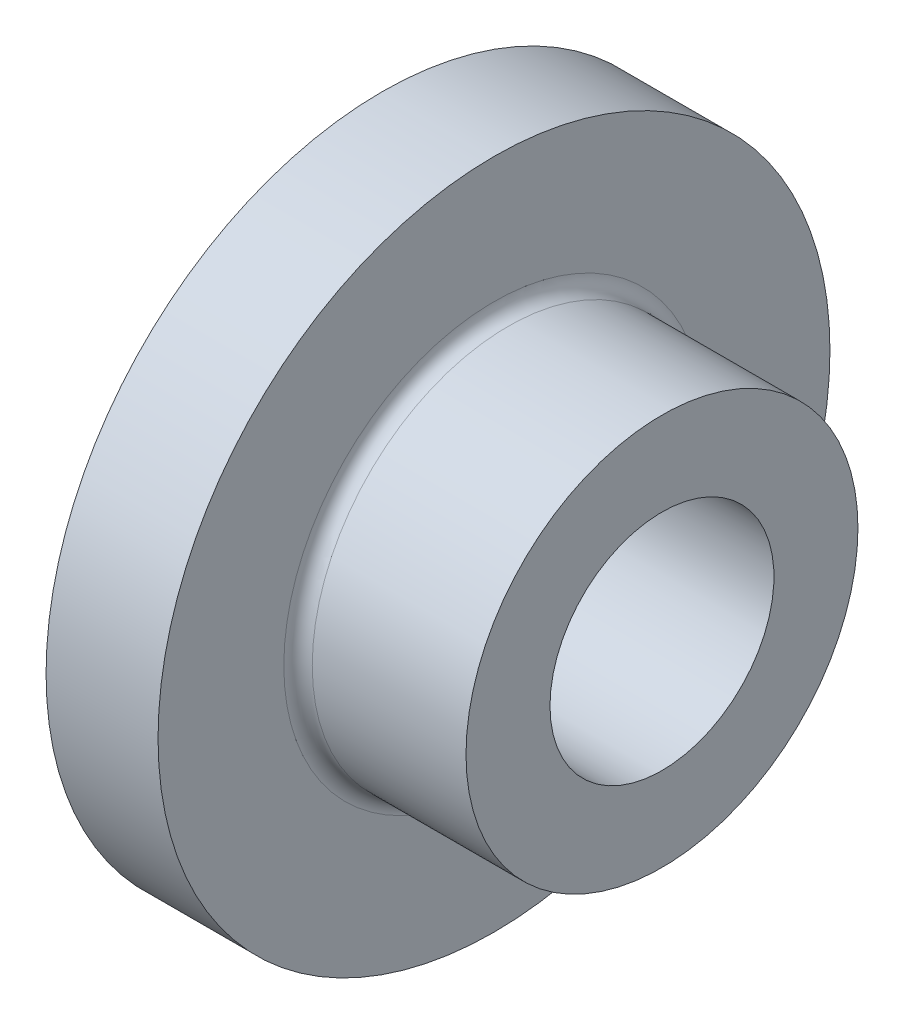
SolidWorks part; units mm, degrees
material "Nylon 101"
ref_plane "Front Plane" through (0, 0, 0) normal (0, 0, 1) x (1, 0, 0)
ref_plane "Top Plane" through (0, 0, 0) normal (0, 1, 0) x (1, 0, 0)
ref_plane "Right Plane" through (0, 0, 0) normal (1, 0, 0) x (0, 0, -1)
sketch "Sketch1" plane through (0, 0, 0) normal (0, 0, 1) x (1, 0, 0)
  line L0 (0, 2) -> (0, 6)
  line L1 (0, 6) -> (2, 6)
  line L2 (2, 6) -> (2, 3.5)
  line L3 (2, 3.5) -> (5, 3.5)
  line L4 (5, 3.5) -> (5, 2)
  line L5 (5, 2) -> (0, 2)
  line L6 (0, 0) -> (7451.5114, 0) construction
  dimension "D1" = 4
  dimension "D2" = 7
  dimension "D3" = 12
  dimension "D4" = 2
  dimension "D5" = 5
revolve "Revolve1" add sketch "Sketch1" angle 360 about L6
fillet "Fillet1" radius 0.254 1 edges at (2, 0, 3.5)
